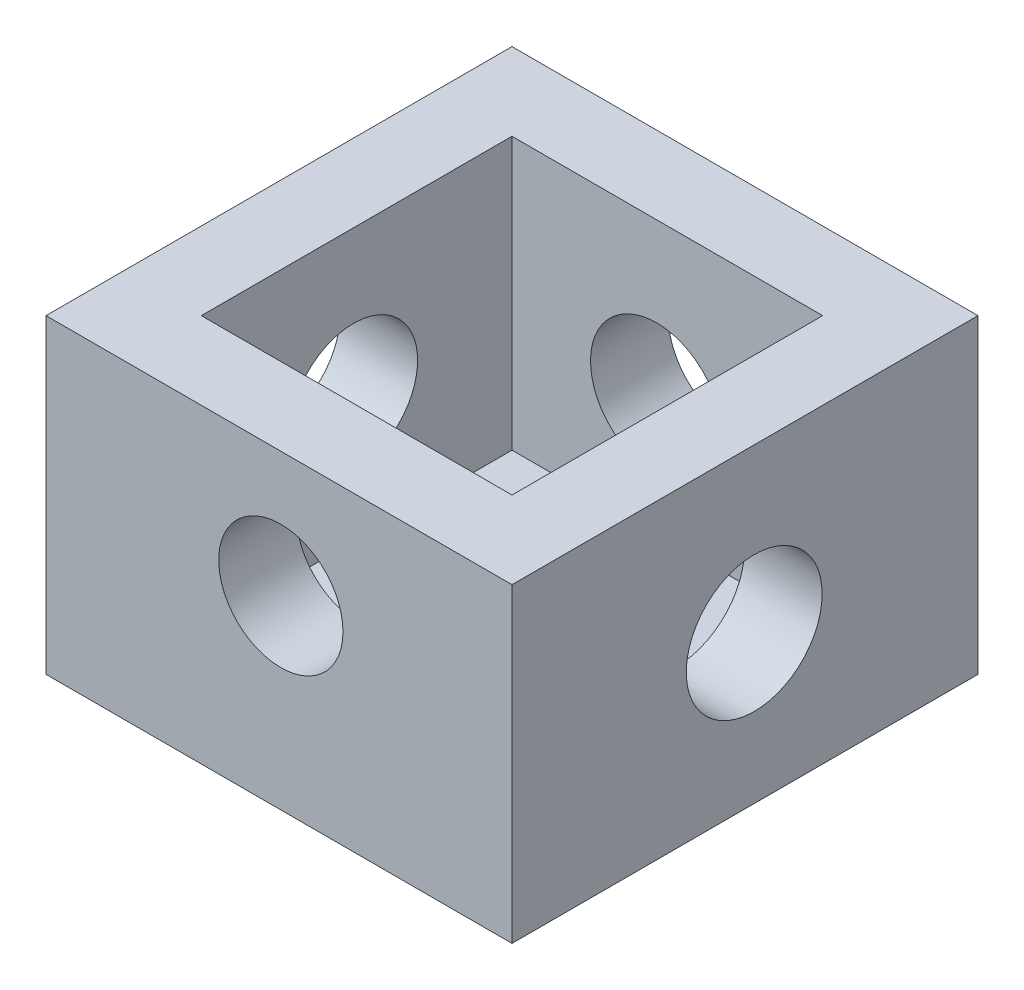
SolidWorks part; units mm, degrees
ref_plane "前基準面" through (0, 0, 0) normal (0, 0, 1) x (1, 0, 0)
ref_plane "上基準面" through (0, 0, 0) normal (0, 1, 0) x (1, 0, 0)
ref_plane "右基準面" through (0, 0, 0) normal (1, 0, 0) x (0, 0, -1)
sketch "草圖1" plane through (0, 0, 0) normal (0, 1, 0) x (1, 0, 0)
  line L1 (-47.6316, 77.2368) -> (12.3684, 77.2368)
  line L2 (-47.6316, 77.2368) -> (-47.6316, 17.2368)
  line L3 (-47.6316, 17.2368) -> (12.3684, 17.2368)
  line L4 (12.3684, 77.2368) -> (12.3684, 17.2368)
  line L5 (-47.6316, 77.2368) -> (12.3684, 17.2368) construction
  line L6 (-47.6316, 17.2368) -> (12.3684, 77.2368) construction
  point P0 (-17.6316, 47.2368)
  dimension "D1" = 60
extrude "填料-伸長2" add sketch "草圖1" along normal blind 40
sketch "草圖2" plane through (0, 40, 0) normal (0, 1, 0) x (1, 0, 0)
  line L0 (-17.6316, 77.2368) -> (-17.6316, 17.2368) construction
  line L1 (-37.6316, 67.2368) -> (2.3684, 67.2368)
  line L2 (-37.6316, 67.2368) -> (-37.6316, 27.2368)
  line L3 (-37.6316, 27.2368) -> (2.3684, 27.2368)
  line L4 (2.3684, 67.2368) -> (2.3684, 27.2368)
  line L5 (-37.6316, 67.2368) -> (2.3684, 27.2368) construction
  line L6 (-37.6316, 27.2368) -> (2.3684, 67.2368) construction
  line L7 (12.3684, 77.2368) -> (-47.6316, 77.2368) construction
  line L8 (-47.6316, 17.2368) -> (12.3684, 17.2368) construction
  point P0 (-17.6316, 47.2368)
  point P5 (-7.6316, 40.9705)
  point P6 (-7.6316, 38.6805)
  point P7 (-7.6316, -2.7632)
  point P14 (-7.6316, 37.2368)
  point P15 (-7.6316, 37.2368)
  dimension "D1" = 40
extrude "除料-伸長1" cut sketch "草圖2" against normal blind 35
hole_wizard "Ø16.0 (16) 直徑孔1" positions "3D草圖3" profile "草圖5" hole size "Ø16.0" standard "ISO"
sketch3d "3D草圖3"
  point P0 (-17.3939, 23.8674, -17.2368)
  point P2 (-17.3939, 23.8674, -17.2368)
sketch "草圖5" plane through (-17.3939, 23.8674, -17.2368) normal (1, 0, 0) x (0, -1, 0)
  line L0 (0, 0) -> (0, 10)
  line L1 (0, 10) -> (8, 10)
  line L2 (8, 10) -> (8, 0)
  line L5 (8, 0) -> (0, 0)
  line L11 (0, -6.35) -> (0, 107.95) construction
  dimension "貫穿孔直徑" = 16
  dimension "貫穿孔深度" = 10
hole_wizard "Ø17.5 (17.5) 直徑孔1" positions "3D草圖4" profile "草圖6" hole size "Ø17.5" standard "ISO"
sketch3d "3D草圖4"
  point P0 (12.3684, 19.0144, -48.4216)
sketch "草圖6" plane through (12.3684, 19.0144, -48.4216) normal (0, 1, 0) x (0, 0, -1)
  line L0 (0, 0) -> (0, 10)
  line L1 (0, 10) -> (8.75, 10)
  line L2 (8.75, 10) -> (8.75, 0)
  line L5 (8.75, 0) -> (0, 0)
  line L11 (0, -6.35) -> (0, 107.95) construction
  dimension "貫穿孔直徑" = 17.5
  dimension "貫穿孔深度" = 10
hole_wizard "Ø16.5 (16.5) 直徑孔1" positions "3D草圖5" profile "草圖7" hole size "Ø16.5" standard "ISO"
sketch3d "3D草圖5"
  point P0 (-47.6316, 21.0933, -46.8351)
sketch "草圖7" plane through (-47.6316, 21.0933, -46.8351) normal (0, 1, 0) x (0, 0, 1)
  line L0 (0, 0) -> (0, 10)
  line L1 (0, 10) -> (8.25, 10)
  line L2 (8.25, 10) -> (8.25, 0)
  line L5 (8.25, 0) -> (0, 0)
  line L11 (0, -6.35) -> (0, 107.95) construction
  dimension "貫穿孔直徑" = 16.5
  dimension "貫穿孔深度" = 10
hole_wizard "Ø17.0 (17) 直徑孔1" positions "3D草圖6" profile "草圖8" hole size "Ø17.0" standard "ISO"
sketch3d "3D草圖6"
  point P0 (-19.0227, 20.0118, -77.2368)
sketch "草圖8" plane through (-19.0227, 20.0118, -77.2368) normal (1, 0, 0) x (0, 1, 0)
  line L0 (0, 0) -> (0, 10)
  line L1 (0, 10) -> (8.5, 10)
  line L2 (8.5, 10) -> (8.5, 0)
  line L5 (8.5, 0) -> (0, 0)
  line L11 (0, -6.35) -> (0, 107.95) construction
  dimension "貫穿孔直徑" = 17
  dimension "貫穿孔深度" = 10
